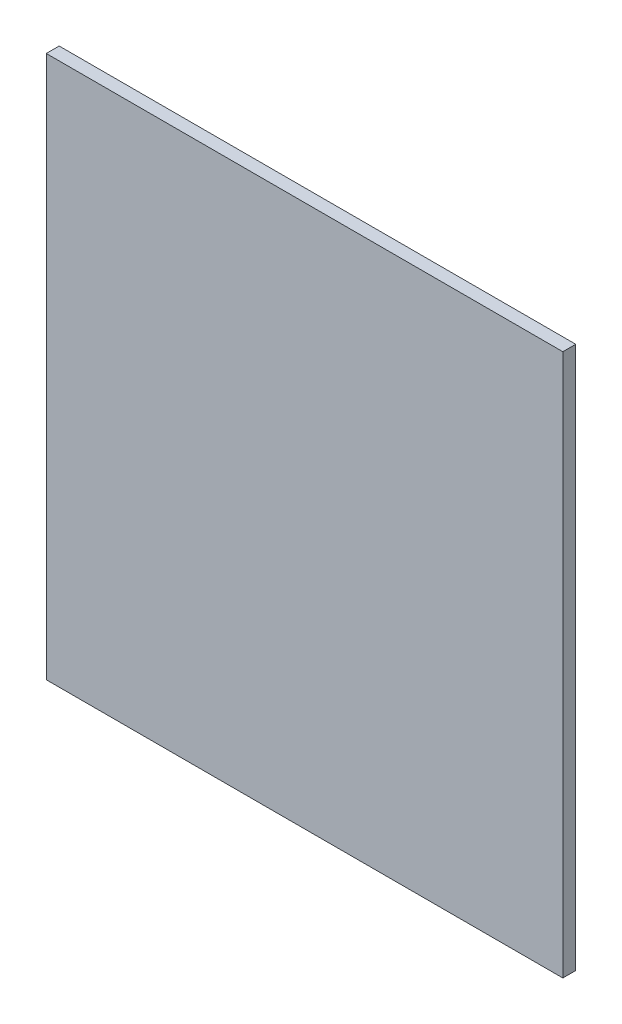
SolidWorks part; units mm, degrees
ref_plane "Front Plane" through (0, 0, 0) normal (0, 0, 1) x (1, 0, 0)
ref_plane "Top Plane" through (0, 0, 0) normal (0, 1, 0) x (1, 0, 0)
ref_plane "Right Plane" through (0, 0, 0) normal (1, 0, 0) x (0, 0, -1)
sketch "Sketch1" plane through (0, 0, 0) normal (0, 0, 1) x (1, 0, 0)
  line L1 (0, 204.7625) -> (190.475, 204.7625)
  line L2 (0, 204.7625) -> (0, 4.7625)
  line L3 (0, 4.7625) -> (190.475, 4.7625)
  line L4 (190.475, 204.7625) -> (190.475, 4.7625)
extrude "Boss-Extrude1" add sketch "Sketch1" against normal blind 4.7625
